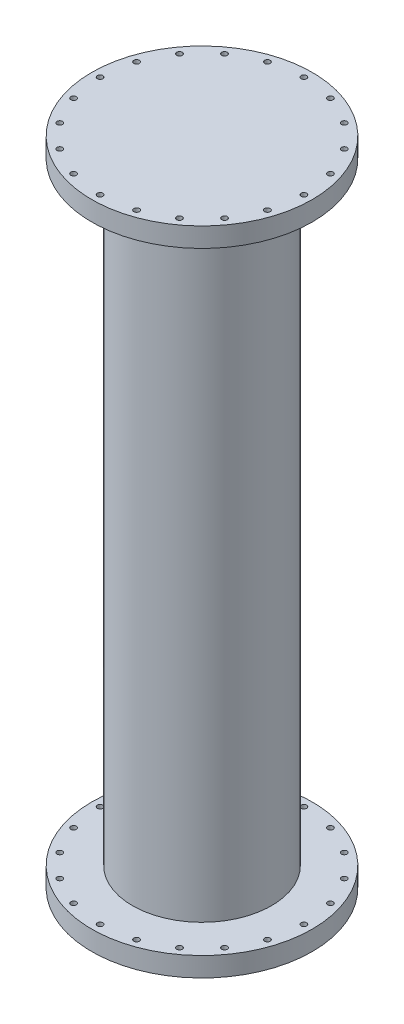
SolidWorks part; units mm, degrees
ref_plane "Plan de face" through (0, 0, 0) normal (0, 0, 1) x (1, 0, 0)
ref_plane "Plan de dessus" through (0, 0, 0) normal (0, 1, 0) x (1, 0, 0)
ref_plane "Plan de droite" through (0, 0, 0) normal (1, 0, 0) x (0, 0, -1)
sketch "Esquisse1" plane through (0, 0, 0) normal (0, 0, 1) x (1, 0, 0)
  line L0 (0, 0) -> (0, -1756.5308) construction
  line L1 (0, 0) -> (396, 0)
  line L2 (0, 0) -> (0, -70)
  line L3 (0, -70) -> (200, -70)
  line L4 (396, 0) -> (396, -70)
  line L26 (250, -70) -> (396, -70)
  line L27 (250, -2270) -> (396, -2270)
  line L29 (200, -70) -> (200, -2270)
  line L31 (250, -70) -> (250, -2270)
  line L32 (0, -2270) -> (200, -2270)
  line L33 (0, -2270) -> (0, -2340)
  line L34 (0, -2340) -> (396, -2340)
  line L35 (396, -2270) -> (396, -2340)
  dimension "D1" = 396
  dimension "D2" = 70
  dimension "D3" = 70
  dimension "D4" = 396
  dimension "D5" = 250
  dimension "D6" = 200
  dimension "D7" = 2200
revolve "Révolution1" add sketch "Esquisse1" angle 360 about L0
sketch "Esquisse2" plane through (0, 0, 0) normal (0, 1, 0) x (1, 0, 0)
  circle A0 centre (366, 0) radius 10
  dimension "D2" = 20
  dimension "D1" = 366
extrude "Enlèv. mat.-Extru.1" cut sketch "Esquisse2" against normal through all
pattern_circular "Répétition circulaire1" count 20 over 360 about axis through (0, 0, 0) along (0, 1, 0) of "Enlèv. mat.-Extru.1"
